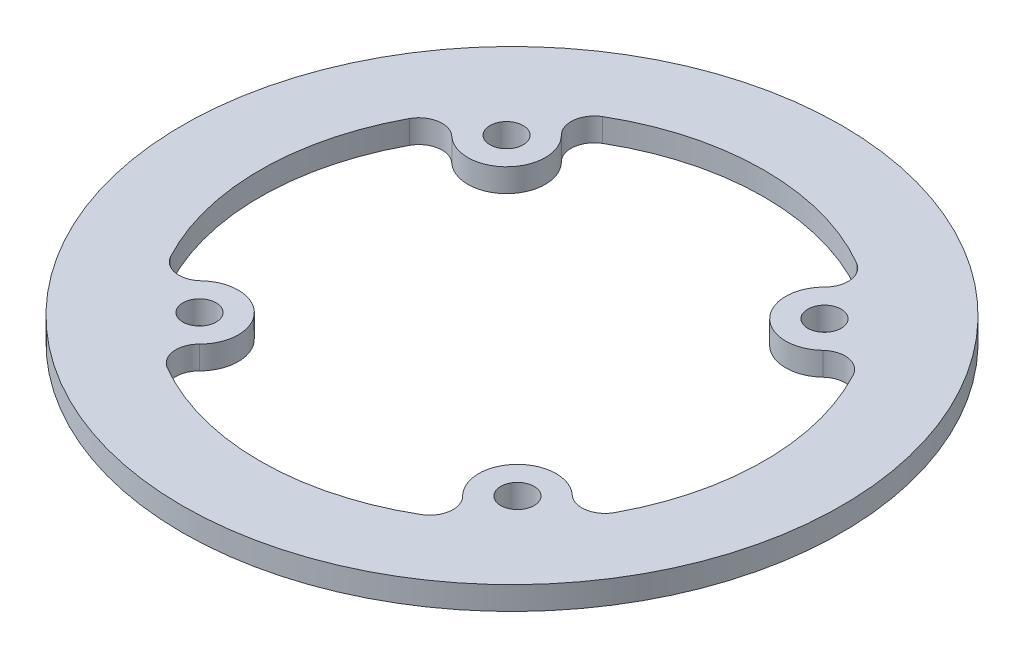
SolidWorks part; units mm, degrees
ref_plane "正面" through (0, 0, 0) normal (0, 0, 1) x (1, 0, 0)
ref_plane "平面" through (0, 0, 0) normal (0, 1, 0) x (1, 0, 0)
ref_plane "右側面" through (0, 0, 0) normal (1, 0, 0) x (0, 0, -1)
sketch "ｽｹｯﾁ1" plane through (0, 0, 0) normal (0, 1, 0) x (1, 0, 0)
  line L0 (0, 0) -> (0, 28.5) construction
  line L1 (0, 0) -> (45, 0) construction
  line L2 (-12, -29) -> (12, -29) construction
  line L3 (-12, -29) -> (-12, 29) construction
  line L4 (-12, 29) -> (12, 29) construction
  line L5 (12, -29) -> (12, 29) construction
  line L6 (-12, -29) -> (12, 29) construction
  line L7 (-12, 29) -> (12, -29) construction
  circle A0 centre (0, 0) radius 28.5 construction
  circle A5 centre (0, 0) radius 45
  circle A7 centre (-20.5, -19.799) radius 6.5 construction
  circle A8 centre (-20.5, -19.799) radius 2
  circle A9 centre (20.5, -19.799) radius 2
  circle A10 centre (20.5, 19.799) radius 2
  circle A11 centre (-20.5, 19.799) radius 2
  dimension "D1" = 57
  dimension "D2" = 58
  dimension "D3" = 24
  dimension "D5" = 90
  dimension "D6" = 8.5
  dimension "D4" = 13
  dimension "D7" = 4
extrude "ﾎﾞｽ - 押し出し1" add sketch "ｽｹｯﾁ1" along normal blind 3
sketch "ｽｹｯﾁ2" plane through (0, 3, 0) normal (0, 1, 0) x (1, 0, 0)
  circle A0 centre (0, 0) radius 32.5
  circle A1 centre (-20.5, -19.799) radius 2 construction
  circle A3 centre (20.5, -19.799) radius 2 construction
  circle A5 centre (20.5, 19.799) radius 2 construction
  circle A7 centre (-20.5, 19.799) radius 2 construction
  circle A9 centre (-20.5, 19.799) radius 5
  circle A13 centre (-20.5, -19.799) radius 2
  circle A14 centre (20.5, -19.799) radius 2
  circle A15 centre (20.5, 19.799) radius 2
  circle A16 centre (-20.5, 19.799) radius 2
  circle A17 centre (-20.5, -19.799) radius 5
  circle A18 centre (20.5, -19.799) radius 5
  circle A19 centre (20.5, 19.799) radius 5
  dimension "D5" = 65
  dimension "D1" = 3
  dimension "D2" = 3
extrude "ｶｯﾄ - 押し出し1" cut sketch "ｽｹｯﾁ2" against normal through all contours A19 A0 A9 A17 A18
fillet "ﾌｨﾚｯﾄ1" radius 3 8 edges at (21.0408, 1.5, -24.7697) (25.4865, 1.5, -20.1666) (25.4865, 1.5, 20.1666) (21.0408, 1.5, 24.7697) (-21.0408, 1.5, 24.7697) (-25.4865, 1.5, 20.1666) (-25.4865, 1.5, -20.1666) (-21.0408, 1.5, -24.7697)
other "面の移動1" face at (0, 3, 45) parameters "D1"=2.5
other "面の移動2" face at (20.5, 3, -17.799) face at (-20.5, 3, -21.799) face at (-20.5, 3, 21.799) face at (20.5, 3, 17.799) parameters "D1"=0.15
